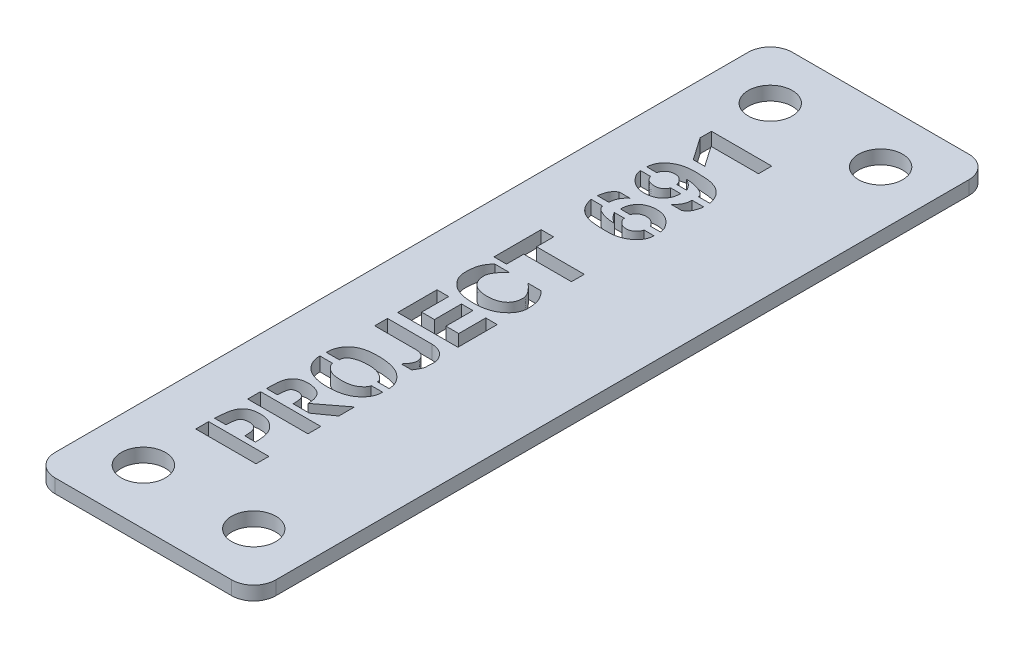
SolidWorks part; units mm, degrees
ref_plane "Front Plane" through (0, 0, 0) normal (0, 0, 1) x (1, 0, 0)
ref_plane "Top Plane" through (0, 0, 0) normal (0, 1, 0) x (1, 0, 0)
ref_plane "Right Plane" through (0, 0, 0) normal (1, 0, 0) x (0, 0, -1)
sketch "Sketch1" plane through (0, 0, 0) normal (0, 1, 0) x (1, 0, 0)
  line L1 (12.7, -42.418) -> (-12.7, -42.418)
  line L2 (12.7, -42.418) -> (12.7, 42.418)
  line L3 (12.7, 42.418) -> (-12.7, 42.418)
  line L4 (-12.7, -42.418) -> (-12.7, 42.418)
  line L5 (12.7, -42.418) -> (-12.7, 42.418) construction
  line L6 (12.7, 42.418) -> (-12.7, -42.418) construction
  point P0 (0, 0)
  dimension "D1" = 84.836
  dimension "D2" = 25.4
extrude "Boss-Extrude1" add sketch "Sketch1" along normal blind 1.5875
fillet "Fillet1" radius 2.54 4 edges at (12.7, 0.7937, 42.418) (-12.7, 0.7937, 42.418) (12.7, 0.7937, -42.418) (-12.7, 0.7937, -42.418)
sketch "Sketch2" plane through (0, 1.5875, 0) normal (0, 1, 0) x (1, 0, 0)
  line L2 (12.7, -39.878) -> (12.7, 39.878) construction
  line L3 (-10.16, -42.418) -> (10.16, -42.418) construction
  line L4 (0, 0) -> (12.7, 0) construction
  line L5 (0, 0) -> (0, -42.418) construction
  circle A0 centre (6.35, 36.068) radius 2.54
  circle A1 centre (-6.35, 36.068) radius 2.54
  circle A2 centre (6.35, -36.068) radius 2.54
  circle A3 centre (-6.35, -36.068) radius 2.54
  dimension "D5" = 5.08
  dimension "D6" = 6.35
  dimension "D7" = 6.35
extrude "Cut-Extrude1" cut sketch "Sketch2" against normal blind 4.7625
sketch "Sketch3" plane through (0, 1.5875, 0) normal (0, 1, 0) x (1, 0, 0)
  line L0 (0, -30.0124) -> (0, 32.7705) construction
  text T0 "PROJECT 691" font "TC_LaserSans" height in points 28
extrude "Cut-Extrude3" cut sketch "Sketch3" against normal blind 4.7625
